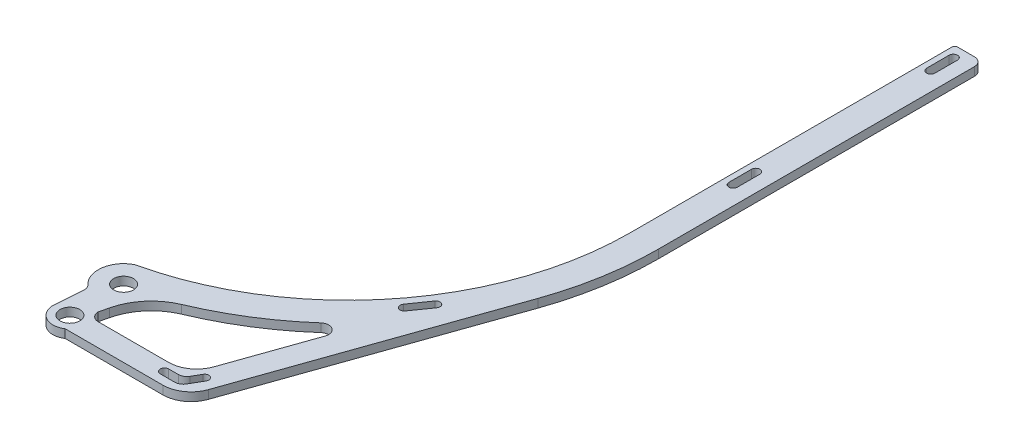
SolidWorks part; units mm, degrees
material "Thornel Mat VMA"
ref_plane "前视基准面" through (0, 0, 0) normal (0, 0, 1) x (1, 0, 0)
ref_plane "上视基准面" through (0, 0, 0) normal (0, 1, 0) x (1, 0, 0)
ref_plane "右视基准面" through (0, 0, 0) normal (1, 0, 0) x (0, 0, -1)
sketch "草图2" plane through (0, 0, 0) normal (0, 1, 0) x (1, 0, 0)
  line L0 (-4, 23) -> (-4, 27)
  line L2 (4, 23) -> (4, 0)
  line L3 (4, 0) -> (-4, 0)
  line L4 (-4, 23) -> (-4, 0)
  line L5 (4, 23) -> (-4, 0) construction
  line L6 (4, 0) -> (-4, 23) construction
  line L7 (4, 23) -> (-4, 23) construction
  line L9 (73.9512, 241.5) -> (83.9512, 241.5)
  line L10 (83.9512, 241.5) -> (83.9512, 124.5)
  line L11 (73.9512, 124.5) -> (73.9512, 241.5)
  line L12 (4, 23) -> (4, 18.7206)
  circle A0 centre (0, 0) radius 5
  circle A1 centre (0, 0) radius 1.5
  circle A2 centre (0, 19) radius 1.5
  arc A5 (-4, 27) -> (73.9512, 124.5) centre (-26, 124.5) ccw
  arc A6 (4, 18.7206) -> (83.9512, 124.5) centre (-26, 124.5) ccw
  point P0 (0, 11.5)
  point P11 (0, 0)
  dimension "D3" = 10
  dimension "D4" = 3
  dimension "D5" = 3
  dimension "D6" = 19
  dimension "D7" = 10
  dimension "D8" = 117
  dimension "D9" = 124.5
  dimension "D10" = 4
  dimension "D1" = 23
  dimension "D2" = 8
  dimension "D11" = 26
extrude "凸台-拉伸1" add sketch "草图2" along normal blind 3
sketch "草图3" plane through (0, 3, 0) normal (0, 1, 0) x (1, 0, 0)
  line L0 (0, -5) -> (45, -5)
  line L1 (45, -5) -> (77.7205, 88.0126)
  line L2 (4, 3) -> (39, 3)
  line L3 (39, 3) -> (55.9577, 51.2046)
  arc A0 (-4, 3) -> (4, 3) centre (0, 0) ccw construction
  arc A1 (4, 18.7206) -> (83.9512, 124.5) centre (-26, 124.5) ccw construction
  circle A3 centre (-26, 124.5) radius 109.9512
  arc M10 (-4, 3) -> (4, 3) centre (0, 0) ccw
  arc M13 (4, 18.7206) -> (83.9512, 124.5) centre (-26, 124.5) ccw
  dimension "D1" = 45
  dimension "D2" = 35
extrude "凸台-拉伸2" add sketch "草图3" against normal blind 3 contours L3 L2 L0 L1 M10 M13
fillet "圆角3" radius 3 1 edges at (55.9577, 1.5, -51.2046)
fillet "圆角4" radius 10 2 edges at (45, 1.5, 5) (39, 1.5, -3)
fillet "圆角5" radius 3 2 edges at (-4, 1.5, -3) (4, 1.5, -3)
sketch "草图4" plane through (0, 3, 0) normal (0, 1, 0) x (1, 0, 0)
  line L0 (40, -0.5) -> (34, -0.5)
  line L1 (40, -0.5) -> (43, 4.6962)
  line L2 (0, -5) -> (37.9171, -5) construction
  line L3 (39.134, 1) -> (41.701, 5.4462)
  line L4 (39.134, 1) -> (34, 1)
  line L5 (40.866, -2) -> (44.299, 3.9462)
  line L6 (40.866, -2) -> (34, -2)
  circle A1 centre (43, 4.6962) radius 1.5
  circle A2 centre (34, -0.5) radius 1.5
  point P6 (37, -0.5)
  dimension "D4" = 40
  dimension "D1" = 6
  dimension "D2" = 6
  dimension "D3" = 0.5
  dimension "D5" = 120
  dimension "D6" = 1.5
  dimension "D7" = 1.5
extrude "切除-拉伸1" cut sketch "草图4" against normal blind 9.5
fillet "圆角6" radius 3 2 edges at (40.866, 1.5, 2) (39.134, 1.5, -1)
sketch "草图5" plane through (0, 3, 0) normal (0, 1, 0) x (1, 0, 0)
  line L0 (61.4861, 68.1247) -> (56.8975, 61.5714) construction
  line L1 (59.1918, 64.8481) -> (-26, 124.5) construction
  line L2 (62.7148, 67.2643) -> (58.1262, 60.7111)
  line L3 (60.2574, 68.985) -> (55.6688, 62.4318)
  line L4 (-26, 124.5) -> (113.9267, 124.5) construction
  circle A0 centre (-26, 124.5) radius 100 construction
  arc A1 (62.7148, 67.2643) -> (60.2574, 68.985) centre (61.4861, 68.1247) ccw
  arc A2 (55.6688, 62.4318) -> (58.1262, 60.7111) centre (56.8975, 61.5714) ccw
  point P7 (59.1918, 64.8481)
  dimension "D1" = 200
  dimension "D3" = 1.5
  dimension "D2" = 8
  dimension "D4" = 35
  dimension "D5" = 104
extrude "切除-拉伸2" cut sketch "草图5" against normal through all
sketch "草图6" plane through (0, 3, 0) normal (0, 1, 0) x (1, 0, 0)
  line L0 (77.4512, 235.5) -> (77.4512, 227.5) construction
  line L1 (73.9512, 124.5) -> (73.9512, 241.5) construction
  line L2 (78.9512, 235.5) -> (78.9512, 227.5)
  line L3 (75.9512, 235.5) -> (75.9512, 227.5)
  line L4 (73.9512, 241.5) -> (83.9512, 241.5) construction
  line L5 (75.9512, 165.5) -> (75.9512, 157.5)
  line L6 (78.9512, 165.5) -> (78.9512, 157.5)
  line L7 (77.4512, 165.5) -> (77.4512, 157.5) construction
  arc A0 (78.9512, 235.5) -> (75.9512, 235.5) centre (77.4512, 235.5) ccw
  arc A1 (75.9512, 227.5) -> (78.9512, 227.5) centre (77.4512, 227.5) ccw
  arc A2 (78.9512, 165.5) -> (75.9512, 165.5) centre (77.4512, 165.5) ccw
  arc A3 (75.9512, 157.5) -> (78.9512, 157.5) centre (77.4512, 157.5) ccw
  point P4 (77.4512, 231.5)
  point P15 (77.4512, 161.5)
  dimension "D2" = 1.5
  dimension "D1" = 2
  dimension "D3" = 8
  dimension "D4" = 10
  dimension "D6" = 70
  dimension "D5" = 2
extrude "切除-拉伸3" cut sketch "草图6" against normal through all
sketch "草图7" plane through (0, 3, 0) normal (0, 1, 0) x (1, 0, 0)
  line L1 (83.9512, 241.5) -> (73.9512, 241.5)
  line L2 (83.9512, 241.5) -> (83.9512, 239.5)
  line L3 (83.9512, 239.5) -> (73.9512, 239.5)
  line L4 (73.9512, 241.5) -> (73.9512, 239.5)
  line L5 (73.9512, 124.5) -> (73.9512, 241.5) construction
  dimension "D1" = 2
  dimension "D2" = 10
extrude "切除-拉伸4" cut sketch "草图7" against normal through all contours L2 L1 L4 L3
fillet "圆角9" radius 1 1 edges at (73.9512, 1.5, -239.5)
fillet "圆角10" radius 3 1 edges at (83.9512, 1.5, -239.5)
sketch "草图8" plane through (0, 3, 0) normal (0, 1, 0) x (1, 0, 0)
  circle A0 centre (0, 0) radius 6
  dimension "D1" = 12
extrude "凸台-拉伸3" add sketch "草图8" against normal blind 3
sketch "草图9" plane through (0, 3, 0) normal (0, 1, 0) x (1, 0, 0)
  circle A0 centre (0, 0) radius 3.5
  dimension "D1" = 7
extrude "切除-拉伸5" cut sketch "草图9" against normal blind 3
sketch "草图10" plane through (0, 3, 0) normal (0, 1, 0) x (1, 0, 0)
  circle A0 centre (0, 19) radius 3.5
  dimension "D1" = 7
extrude "切除-拉伸6" cut sketch "草图10" against normal blind 3
sketch "草图12" plane through (0, 3, 0) normal (0, 1, 0) x (1, 0, 0)
  line L0 (4, 6) -> (4, 18.7206)
  line L1 (4, 18.7206) -> (7.4641, 20.7206)
  line L2 (7.4641, 20.7206) -> (4, 6)
  dimension "D1" = 4
  dimension "D2" = 120
extrude "凸台-拉伸6" add sketch "草图12" against normal blind 3
sketch "草图14" plane through (0, 3, 0) normal (0, 1, 0) x (1, 0, 0)
  line L0 (-4, 27) -> (-6, 0)
  line L1 (-6, 0) -> (-4, 4.4721)
  line L2 (-4, 4.4721) -> (-4, 27)
  arc A0 (-4, 4.4721) -> (3.3166, -5) centre (0, 0) ccw construction
extrude "凸台-拉伸7" add sketch "草图14" against normal blind 3
sketch "草图15" plane through (0, 3, 0) normal (0, 1, 0) x (1, 0, 0)
  line L0 (-4, 27) -> (-5.1351, 11.6767)
  line L1 (-4, 27) -> (-5.9345, 0.884) construction
  circle A0 centre (0, 19) radius 8.9443
  line M12 (-4, 27) -> (-5.9345, 0.884)
extrude "凸台-拉伸8" add sketch "草图15" against normal blind 3 contours A0 M12
fillet "圆角12" radius 3 2 edges at (-5.1351, 1.5, -11.6767) (-4, 1.5, -27)
fillet "圆角13" radius 20 1 edges at (7.221, 1.5, -19.6876)
